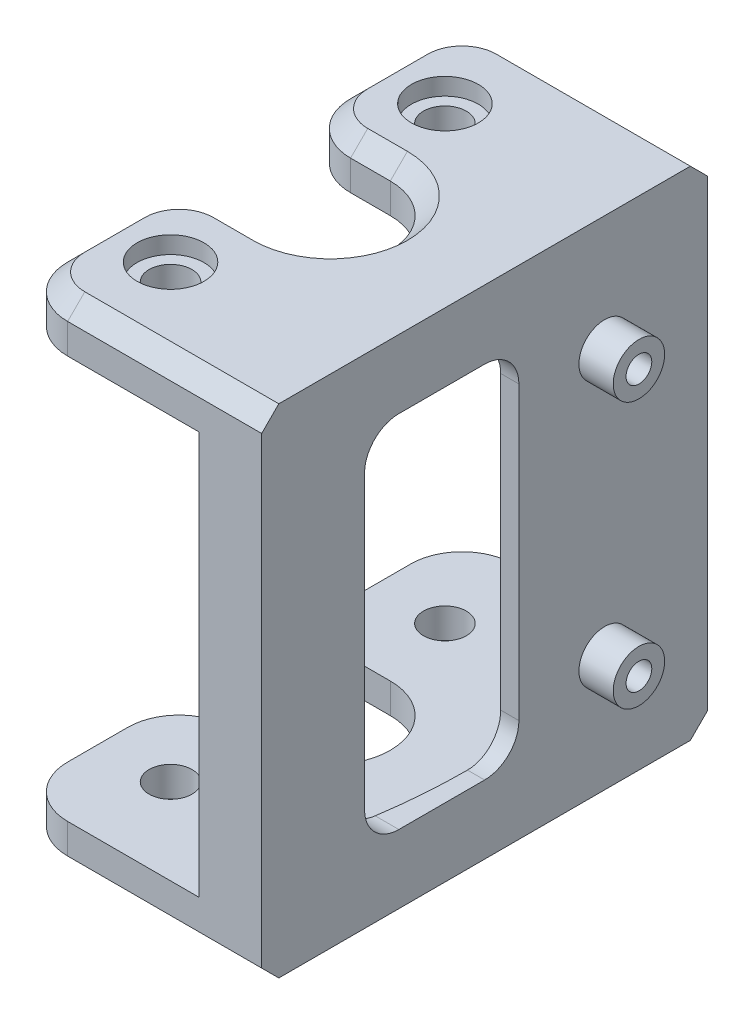
SolidWorks part; units mm, degrees
ref_plane "Спереди" through (0, 0, 0) normal (0, 0, 1) x (1, 0, 0)
ref_plane "Сверху" through (0, 0, 0) normal (0, 1, 0) x (1, 0, 0)
ref_plane "Справа" through (0, 0, 0) normal (1, 0, 0) x (0, 0, -1)
sketch "Эскиз1" plane through (0, 0, 0) normal (0, 1, 0) x (1, 0, 0)
  line L0 (23.6854, 8) -> (23.6854, -8) construction
  line L1 (19.6854, 13) -> (34, 13)
  line L2 (19.6854, 13) -> (19.6854, -13)
  line L3 (19.6854, -13) -> (34, -13)
  line L4 (34, 13) -> (34, -13)
  line L5 (19.6854, 13) -> (34, -13) construction
  line L6 (19.6854, -13) -> (34, 13) construction
  line L7 (25, 3.5) -> (19.6854, 3.5)
  line L8 (25, -3.5) -> (19.6854, -3.5)
  circle A0 centre (0, 0) radius 25 construction
  circle A1 centre (23.6854, 8) radius 1.25
  circle A2 centre (23.6854, -8) radius 1.25
  circle A3 centre (25, 0) radius 3.5
  point P3 (26.8427, 0)
  dimension "D1" = 50
  dimension "D2" = 2.5
  dimension "D3" = 2.5
  dimension "D8" = 7
  dimension "D4" = 16
  dimension "D5" = 4
  dimension "D6" = 34
  dimension "D7" = 26
extrude "Бобышка-Вытянуть1" add sketch "Эскиз1" along normal mid plane 29 contours A3 L8 L2 L3 L4 L1 L7 A2 A1
sketch "Эскиз2" plane through (0, 0, 0) normal (0, 1, 0) x (1, 0, 0)
  circle A0 centre (0, 0) radius 33
  dimension "D1" = 66
extrude "Вырез-Вытянуть1" cut sketch "Эскиз2" against normal mid plane 23.5 contours A0
sketch "Эскиз3" plane through (34, 0, 0) normal (1, 0, 0) x (0, 0, -1)
  line L0 (-13, 0) -> (13, 0) construction
  line L5 (-7, 10.5) -> (2, 10.5)
  line L6 (-7, 10.5) -> (-7, -10.5)
  line L7 (-7, -10.5) -> (2, -10.5)
  line L8 (2, 10.5) -> (2, -10.5)
  line L9 (-7, 10.5) -> (2, -10.5) construction
  line L10 (-7, -10.5) -> (2, 10.5) construction
  line L11 (-13, 14.5) -> (-13, -14.5) construction
  line L12 (13, 14.5) -> (13, -14.5) construction
  circle A0 centre (7, 7.75) radius 0.75
  circle A1 centre (7, -7.75) radius 0.75
  point P0 (-2.5, 0)
  dimension "D5" = 1.5
  dimension "D1" = 6
  dimension "D2" = 5
  dimension "D3" = 21
  dimension "D4" = 6
  dimension "D6" = 15.5
extrude "Вырез-Вытянуть2" cut sketch "Эскиз3" against normal through all
sketch "Эскиз4" plane through (34, 0, 0) normal (1, 0, 0) x (0, 0, -1)
  circle A0 centre (7, 7.75) radius 1.5
  circle A1 centre (7, -7.75) radius 1.5
  circle A11 centre (7, 7.75) radius 0.75
  circle A12 centre (7, 7.75) radius 0.75
  circle A14 centre (7, -7.75) radius 0.75
  circle A15 centre (7, -7.75) radius 0.75
  dimension "D1" = 3
  dimension "D2" = 3
  dimension "D4" = 0
extrude "Бобышка-Вытянуть2" add sketch "Эскиз4" along normal blind 2
fillet "Скругление1" radius 2 4 edges at (33.4697, -10.5, -2) (33.4697, 10.5, -2) (33.1245, 10.5, 7) (33.1245, -10.5, 7)
fillet "Скругление2" radius 3 8 edges at (19.6854, -13.125, -13) (19.6854, -13.125, -3.5) (19.6854, -13.125, 3.5) (19.6854, -13.125, 13) (19.6854, 13.125, -13) (19.6854, 13.125, -3.5) (19.6854, 13.125, 3.5) (19.6854, 13.125, 13)
chamfer "Фаска1" distance 1 angle 45 22 edges at (28.3427, -14.5, -13) (20.5641, -14.5, -12.1213) (19.6854, -14.5, -8.25) (20.5641, -14.5, -4.3787) (23.8427, -14.5, -3.5) (28.5, -14.5, 0) (23.8427, -14.5, 3.5) (20.5641, -14.5, 4.3787) (19.6854, -14.5, 8.25) (20.5641, -14.5, 12.1213) (28.3427, -14.5, 13) (28.3427, 14.5, -13) (20.5641, 14.5, -12.1213) (19.6854, 14.5, -8.25) (20.5641, 14.5, -4.3787) (23.8427, 14.5, -3.5) (28.5, 14.5, 0) (23.8427, 14.5, 3.5) (20.5641, 14.5, 4.3787) (19.6854, 14.5, 8.25) (20.5641, 14.5, 12.1213) (28.3427, 14.5, 13)
sketch "Эскиз5" plane through (0, 14.5, 0) normal (0, 1, 0) x (1, 0, 0)
  circle A0 centre (23.6854, -8) radius 1.95
  circle A1 centre (23.6854, 8) radius 1.95
  dimension "D1" = 3.9
  dimension "D2" = 3.9
extrude "Вырез-Вытянуть3" cut sketch "Эскиз5" against normal blind 1
mirror "Зеркальное отражение1" about plane through (0, 0, 0) normal (0, 1, 0) of "Вырез-Вытянуть3"
equation "\"motor_diameter\"= 30"
equation "\"mm_diameter\"= IIF ( \"motor_diameter\" < 34 , 41 , \"motor_diameter\" + 8 )"
equation "\"upper_shafts_diameter\"= 5"
equation "\"upper_shats_length\"= 180"
equation "\"upper_bearing_d1\"= 10"
equation "\"upper_bearing_d2\"= 5"
equation "\"upper_bearing_h\"= 15"
equation "\"lower_shafts_diameter\"= 5"
equation "\"lower_shafts_length\"= 180"
equation "\"lower_bearing_d1\"= 10"
equation "\"lower_bearing_d2\"= 5"
equation "\"lower_bearing_h\"= 15"
equation "\"print_offset\"= 0.5"
equation "\"bh_screws_d\"= 2"
equation "\"bh_screws_h\"= 20"
equation "\"bh_screws_hh_d\"= 3.4"
equation "\"bh_screws_hh_h\"= 2"
equation "\"bh_nut_d\"= 3.8"
equation "\"bh_nut_h\"= 2"
equation "\"motor_screws_d\"= 3"
equation "\"motor_screws_h\"= 16"
equation "\"motor_screws_hh_d\"= 5.5"
equation "\"motor_screws_hh_h\"= 3"
equation "\"plate_hole_distance\"= 25.4"
equation "\"plate_screws_d\"= 6.5"
equation "\"shafts_diameter\"= IIF ( \"mm_diameter\" < 42 , 42 + 8 , \"mm_diameter\" + 8 )"
equation "\"central_hole_diameter\"= 8"
equation "\"bh_thikness\"= 4"
equation "\"ends_screws_d\"= 4"
equation "\"ends_screws_h\"= 16"
equation "\"ends_screws_hh_d\"= 6.7"
equation "\"ends_screws_hh_h\"= 4.1"
equation "\"ends_nut_d\"= 6.8"
equation "\"ends_nut_h\"= 3"
equation "\"system_radius\" = ( \"shafts_diameter\" + 12 + \"bh_thikness\" / 2 ) / 2"
equation "\"encoder_distance\"= \"system_radius\" + 4"
equation "\"tape_position\"= \"encoder_distance\" - 2 + 3.9 + 1.7 / 2"
equation "\"D1@Эскиз1\"=\"shafts_diameter\""
equation "\"D2@Эскиз1\"=\"bh_screws_d\"+\"print_offset\""
equation "\"D3@Эскиз1\"=\"D2@Эскиз1\""
equation "\"D5@Эскиз1\"=\"bh_thikness\""
equation "\"D6@Эскиз1\"=\"encoder_distance\"-2"
equation "\"D8@Эскиз1\"=\"lower_shafts_diameter\"+2"
equation "\"D1@Бобышка-Вытянуть1\"=\"lower_bearing_h\"+\"bh_thikness\"*2+6"
equation "\"D1@Эскиз2\"=\"system_radius\"*2+2"
equation "\"D1@Вырез-Вытянуть1\"=\"lower_bearing_h\"+\"print_offset\"+\"bh_thikness\"*2"
equation "\"D5@Эскиз3\"=\"bh_screws_d\"-\"print_offset\""
equation "\"D2@Эскиз4\"=\"D1@Эскиз4\""
equation "\"D1@Эскиз5\"=\"bh_screws_hh_d\"+\"print_offset\""
equation "\"D2@Эскиз5\"=\"D1@Эскиз5\""
